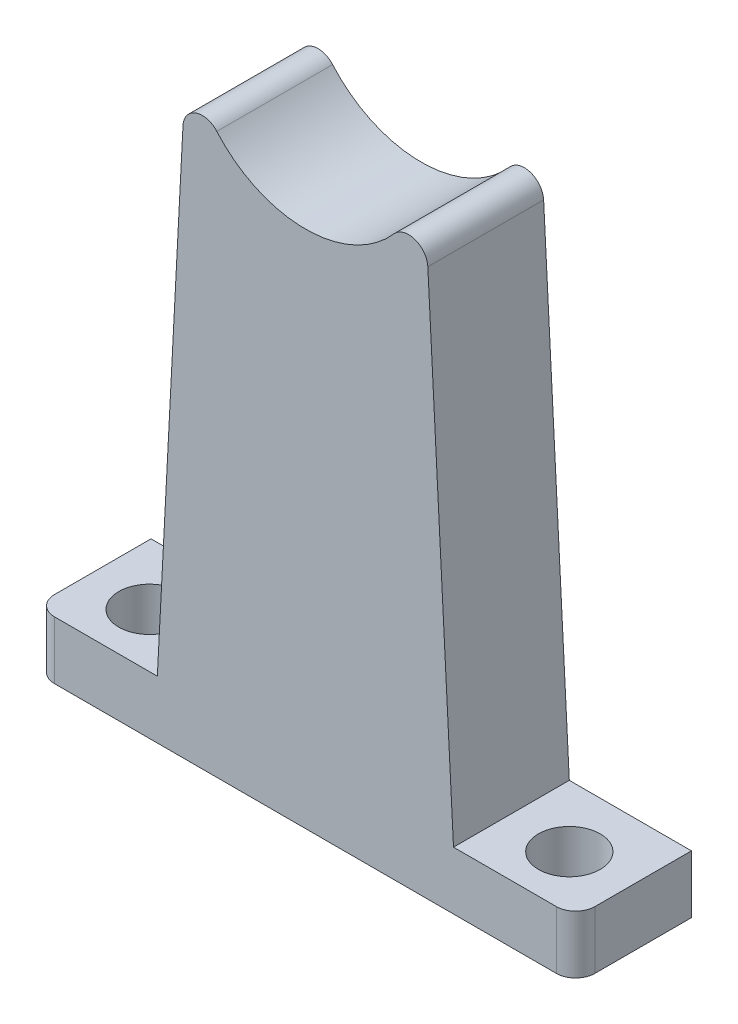
SolidWorks part; units mm, degrees
ref_plane "Front Plane" through (0, 0, 0) normal (0, 0, 1) x (1, 0, 0)
ref_plane "Top Plane" through (0, 0, 0) normal (0, 1, 0) x (1, 0, 0)
ref_plane "Right Plane" through (0, 0, 0) normal (1, 0, 0) x (0, 0, -1)
sketch "Sketch1" plane through (0, 0, 0) normal (0, 0, 1) x (1, 0, 0)
  line L0 (0, 0) -> (0, -26.4) construction
  line L2 (-6.1, -32.5) -> (-6.1, -65) construction
  line L3 (0, -38.6) -> (0, -65) construction
  line L4 (6.1, -32.5) -> (6.1, -65) construction
  line L5 (-6.3423, -37.1227) -> (-7.6722, -62.5)
  line L6 (6.3423, -37.1227) -> (7.6722, -62.5)
  line L9 (-14, -62.5) -> (-7.6722, -62.5)
  line L10 (-14, -62.5) -> (-14, -65.5)
  line L11 (-14, -65.5) -> (14, -65.5)
  line L12 (14, -62.5) -> (14, -65.5)
  line L13 (7.6722, -62.5) -> (14, -62.5)
  arc A1 (-4.591, -36.5165) -> (4.591, -36.5165) centre (0, -32.5) ccw
  arc A2 (-4.591, -36.5165) -> (-6.3423, -37.1227) centre (-5.3436, -37.175) ccw
  arc A3 (4.591, -36.5165) -> (6.3423, -37.1227) centre (5.3436, -37.175) cw
  dimension "D1" = 1
  dimension "D3" = 1
  dimension "D2" = 3
  dimension "D4" = 3
  dimension "D5" = 33
  dimension "D6" = 28
  dimension "D7" = 14
extrude "Boss-Extrude1" add sketch "Sketch1" along normal blind 6
sketch "Sketch2" plane through (0, -65.5, 0) normal (0, -1, 0) x (1, 0, 0)
  circle A0 centre (10.8722, 3.2) radius 1.6
  circle A1 centre (-10.8722, 3.2) radius 1.6
  dimension "D1" = 3.2
extrude "Cut-Extrude1" cut sketch "Sketch2" against normal blind 10
fillet "Fillet1" radius 1
